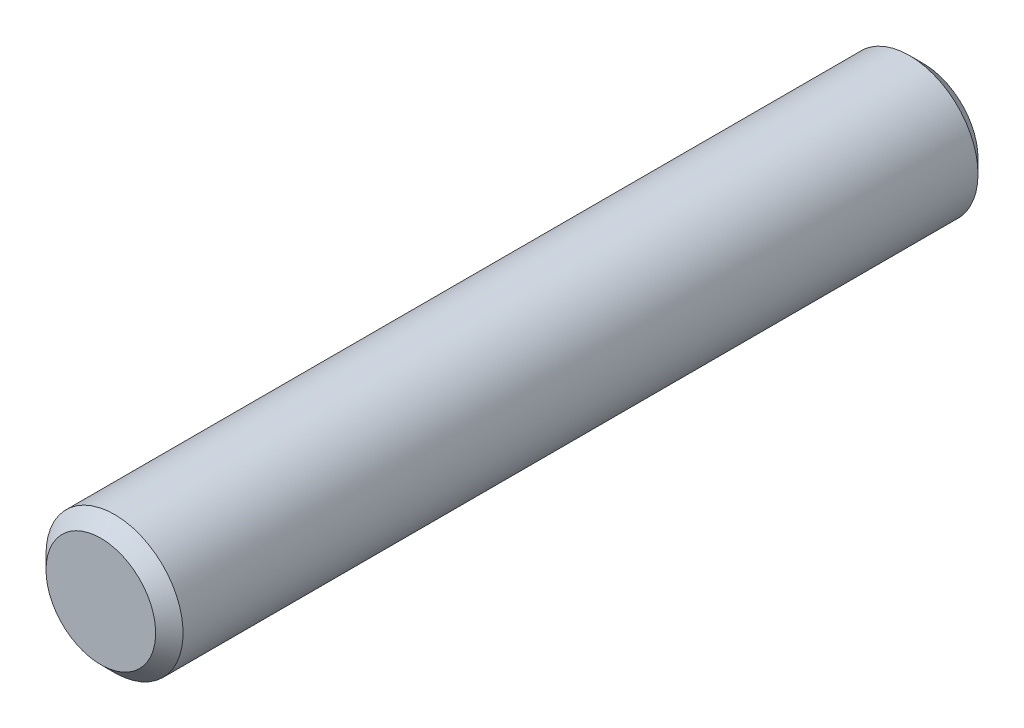
SolidWorks part; units mm, degrees
ref_plane "Front" through (0, 0, 0) normal (0, 0, 1) x (1, 0, 0)
ref_plane "Top" through (0, 0, 0) normal (0, 1, 0) x (1, 0, 0)
ref_plane "Right" through (0, 0, 0) normal (1, 0, 0) x (0, 0, -1)
sketch "Sketch1" plane through (0, 0, 0) normal (0, 0, 1) x (1, 0, 0)
  circle A0 centre (0, 0) radius 3.175
  dimension "dia" = 6.35
extrude "Extrude1" add sketch "Sketch1" along normal mid plane 38.1
sketch "Sketch2" plane through (0, 0, 0) normal (1, 0, 0) x (0, 0, -1)
  point P0 (-19.05, 3.175)
  point P1 (19.05, 3.175)
chamfer "Chamfer1" distance 0.635 angle 45 2 edges at (3.175, 0, -19.05) (3.175, 0, 19.05)
equation "\"D1@Chamfer1\" = \"dia@Sketch1\" * .1"
